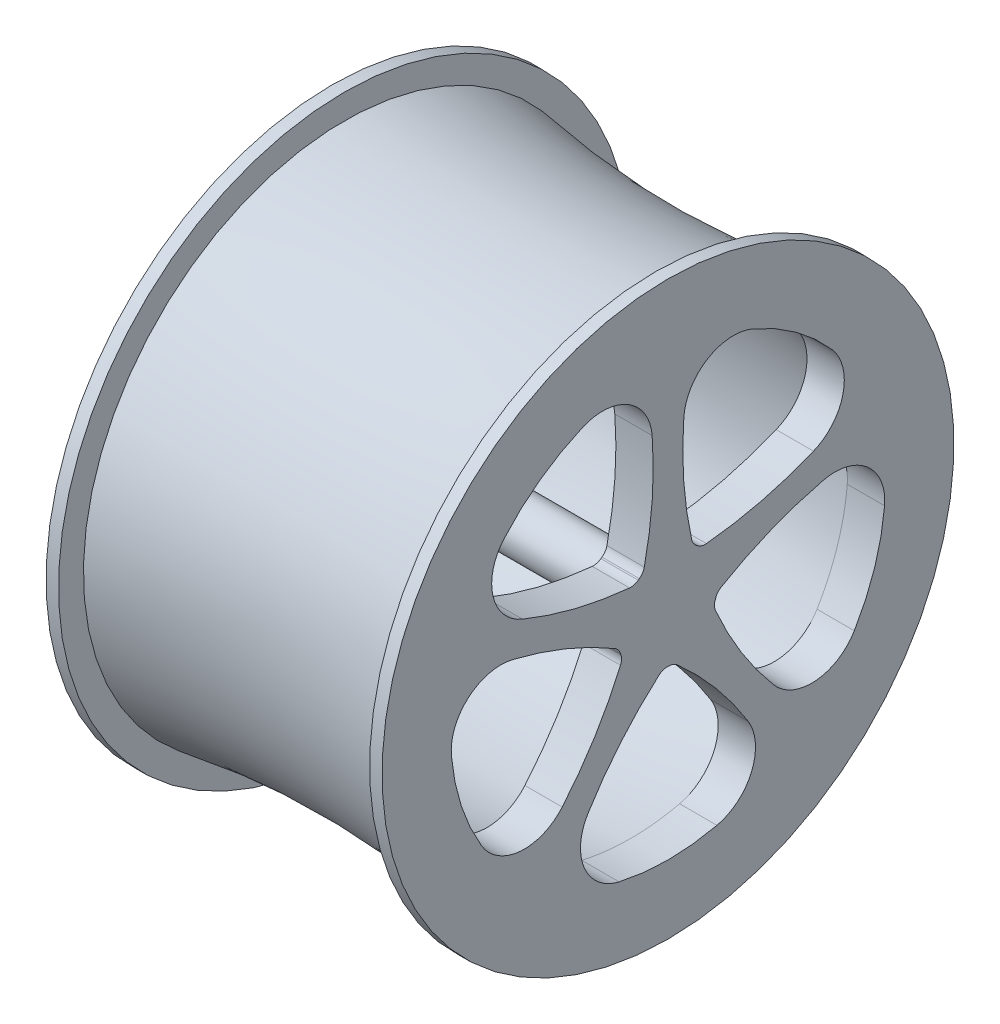
SolidWorks part; units mm, degrees
ref_plane "Front Plane" through (0, 0, 0) normal (0, 0, 1) x (1, 0, 0)
ref_plane "Top Plane" through (0, 0, 0) normal (0, 1, 0) x (1, 0, 0)
ref_plane "Right Plane" through (0, 0, 0) normal (1, 0, 0) x (0, 0, -1)
sketch "Sketch1" plane through (0, 0, 0) normal (0, 0, 1) x (1, 0, 0)
  line L0 (0, -11.7761) -> (0, 20.98) construction
  line L1 (1.5, 0) -> (18.5, 0)
  line L2 (-8.5, 20.98) -> (-8.5, 17.48)
  line L3 (-8.5, 17.48) -> (-7.5, 17.48)
  line L4 (15.5, 17.48) -> (15.5, 2)
  line L6 (-8.5, 2) -> (-8.5, 1)
  line L7 (-8.5, 2) -> (15.5, 2)
  line L8 (-7.5, 20.98) -> (-7.5, 17.48)
  line L10 (18.5, 0) -> (18.5, 20.98)
  line L14 (-8.5, 20.98) -> (-8.5, 22.98)
  line L15 (-8.5, 22.98) -> (-7.5, 22.98)
  line L16 (-7.5, 22.98) -> (-7.5, 20.98)
  line L17 (18.5, 20.98) -> (18.5, 22.98)
  line L18 (18.5, 22.98) -> (17.5, 22.98)
  line L19 (17.5, 22.98) -> (17.5, 20.98)
  line L21 (-8.5, 1) -> (1.5, 1)
  line L22 (1.5, 1) -> (1.5, 0)
  arc A0 (-7.5, 20.98) -> (17.5, 20.98) centre (5, 98.0044) ccw
  arc A1 (-7.5, 17.48) -> (15.5, 17.48) centre (4, -69.5312) cw
  dimension "D6" = 2
  dimension "D9" = 3
  dimension "D10" = 10
  dimension "D1" = 27
  dimension "D2" = 20.98
  dimension "D3" = 1
  dimension "D4" = 1
  dimension "D5" = 24
  dimension "D7" = 2
  dimension "D8" = 3.5
revolve "Revolve1" add sketch "Sketch1" angle 360 about L1
sketch "Sketch2" plane through (18.5, 0, 0) normal (1, 0, 0) x (0, 0, -1)
  line L0 (2, 17.3564) -> (2.0018, 17.364)
  line L1 (2.0018, 17.364) -> (2, 17.3564)
  line L5 (-2, 17.3652) -> (-2, 17.3564)
  arc A0 (12.4791, 2.7163) -> (4.2671, -0.6187) centre (19.5374, -26.4415) ccw
  arc A1 (2.3955, 3.2034) -> (2.3064, 3.2681) centre (0, 0) ccw
  arc A2 (17.4051, -1.5192) -> (12.4791, 2.7163) centre (13.4202, -1.1714) ccw
  arc A3 (1.2729, 12.7078) -> (1.907, 3.8671) centre (31.1848, 10.4103) ccw
  arc A4 (11.6925, 5.1375) -> (3.0885, 3.0087) centre (0.2641, 32.8754) cw
  arc A5 (8.4992, -9.5326) -> (3.8158, -2.0076) centre (31.348, 9.9079) cw
  arc A6 (14.974, -9.0014) -> (8.4992, -9.5326) centre (11.5457, -6.9405) cw
  arc A7 (14.974, -9.0014) -> (17.4051, -1.5192) centre (0, 0) ccw
  arc A8 (3.8158, -2.0076) -> (3.7868, -1.2883) centre (4.7336, -1.6104) cw
  arc A9 (3.8209, -1.1836) -> (4.2671, -0.6187) centre (4.7761, -1.4795) cw
  arc A10 (6.4397, -11.029) -> (0.7302, -4.2494) centre (-19.11, -26.752) ccw
  arc A11 (3.9336, -17.0227) -> (6.4397, -11.029) centre (3.033, -13.1254) ccw
  arc A12 (2.3064, 3.2681) -> (1.907, 3.8671) centre (2.8829, 4.0852) cw
  arc A13 (3.0885, 3.0087) -> (2.3955, 3.2034) centre (2.9943, 4.0042) cw
  arc A14 (13.188, 11.4595) -> (6.8233, 16.0838) centre (0, 0) ccw
  arc A15 (13.188, 11.4595) -> (11.6925, 5.1375) centre (10.1687, 8.8359) cw
  arc A16 (6.8233, 16.0838) -> (1.2729, 12.7078) centre (5.2611, 12.4014) ccw
  arc A17 (-6.4397, -11.029) -> (-0.7302, -4.2494) centre (19.11, -26.752) cw
  arc A18 (-3.9336, -17.0227) -> (-6.4397, -11.029) centre (-3.033, -13.1254) cw
  arc A19 (-3.9336, -17.0227) -> (3.9336, -17.0227) centre (0, 0) ccw
  arc A20 (-0.7302, -4.2494) -> (-0.0551, -3.9996) centre (-0.0688, -4.9995) cw
  arc A21 (0.0551, -3.9996) -> (0.7302, -4.2494) centre (0.0688, -4.9995) cw
  arc A22 (-8.4992, -9.5326) -> (-3.8158, -2.0076) centre (-31.348, 9.9079) ccw
  arc A23 (-14.974, -9.0014) -> (-8.4992, -9.5326) centre (-11.5457, -6.9405) ccw
  arc A24 (-12.4791, 2.7163) -> (-4.2671, -0.6187) centre (-19.5374, -26.4415) cw
  arc A25 (-17.4051, -1.5192) -> (-12.4791, 2.7163) centre (-13.4202, -1.1714) cw
  arc A26 (-17.4051, -1.5192) -> (-14.974, -9.0014) centre (0, 0) ccw
  arc A27 (-4.2671, -0.6187) -> (-3.8209, -1.1836) centre (-4.7761, -1.4795) cw
  arc A28 (-3.7868, -1.2883) -> (-3.8158, -2.0076) centre (-4.7336, -1.6104) cw
  arc A29 (-11.6925, 5.1375) -> (-3.0885, 3.0087) centre (-0.2641, 32.8754) ccw
  arc A30 (-13.188, 11.4595) -> (-11.6925, 5.1375) centre (-10.1687, 8.8359) ccw
  arc A31 (-1.2729, 12.7078) -> (-1.907, 3.8671) centre (-31.1848, 10.4103) cw
  arc A32 (-6.8233, 16.0838) -> (-1.2729, 12.7078) centre (-5.2611, 12.4014) cw
  arc A33 (-6.8233, 16.0838) -> (-13.188, 11.4595) centre (0, 0) ccw
  arc A34 (-1.907, 3.8671) -> (-2.3064, 3.2681) centre (-2.8829, 4.0852) cw
  arc A35 (-2.3955, 3.2034) -> (-3.0885, 3.0087) centre (-2.9943, 4.0042) cw
  point P7 (-2, 17.48)
  point P8 (-2, 4)
  point P16 (0, 0)
  point P40 (0, 0)
  point P44 (15.8889, 7.2655)
  point P84 (0, 0)
  dimension "D1" = 5
  dimension "D3" = 1
  dimension "D2" = 1
  dimension "D4" = 4
  dimension "D5" = 4
extrude "Cut-Extrude1" cut sketch "Sketch2" against normal blind 10 contours A3 A12 A1 A13 A4 A15 A14 A16
pattern_circular "CirPattern1" count 5 over 360 about axis through (0, 0, 0) along (1, 0, 0) of "Cut-Extrude1"
